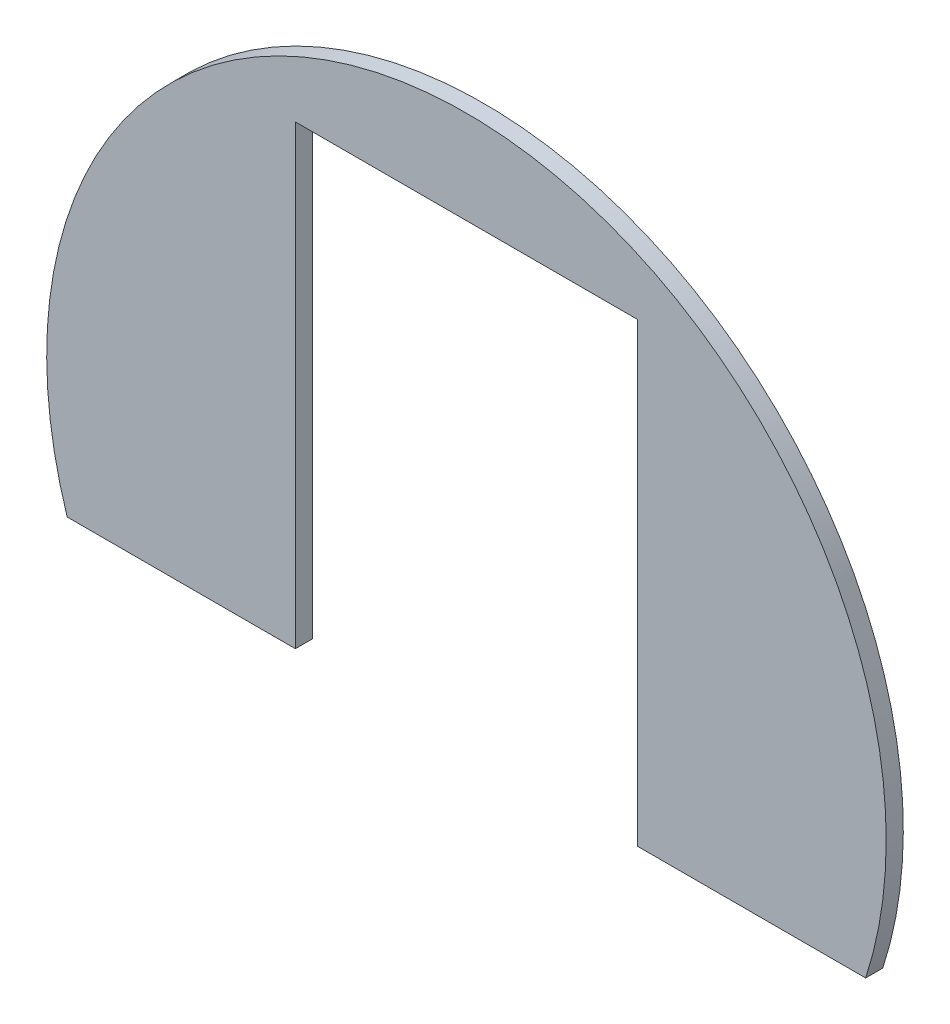
SolidWorks part; units mm, degrees
ref_plane "Front Plane" through (0, 0, 0) normal (0, 0, 1) x (1, 0, 0)
ref_plane "Top Plane" through (0, 0, 0) normal (0, 1, 0) x (1, 0, 0)
ref_plane "Right Plane" through (0, 0, 0) normal (1, 0, 0) x (0, 0, -1)
sketch "Sketch1" plane through (0, 0, 0) normal (0, 0, 1) x (1, 0, 0)
  line L0 (-1778, -577.5136) -> (1778, -577.5136)
  line L1 (0, 1869.44) -> (0, -1869.44) construction
  line L2 (-762, -577.5136) -> (762, -577.5136)
  line L3 (-762, -577.5136) -> (-762, 1454.4864)
  line L4 (-762, 1454.4864) -> (762, 1454.4864)
  line L5 (762, -577.5136) -> (762, 1454.4864)
  circle A0 centre (0, 0) radius 1869.44
  point P11 (0, 1454.4864)
  dimension "D1" = 3738.88
  dimension "D2" = 3556
  dimension "D3" = 2032
  dimension "D4" = 1524
extrude "Boss-Extrude1" add sketch "Sketch1" along normal blind 76.2 contours A0 L1 L4 L5 L0 | L1 A0 L0 L3 L4
